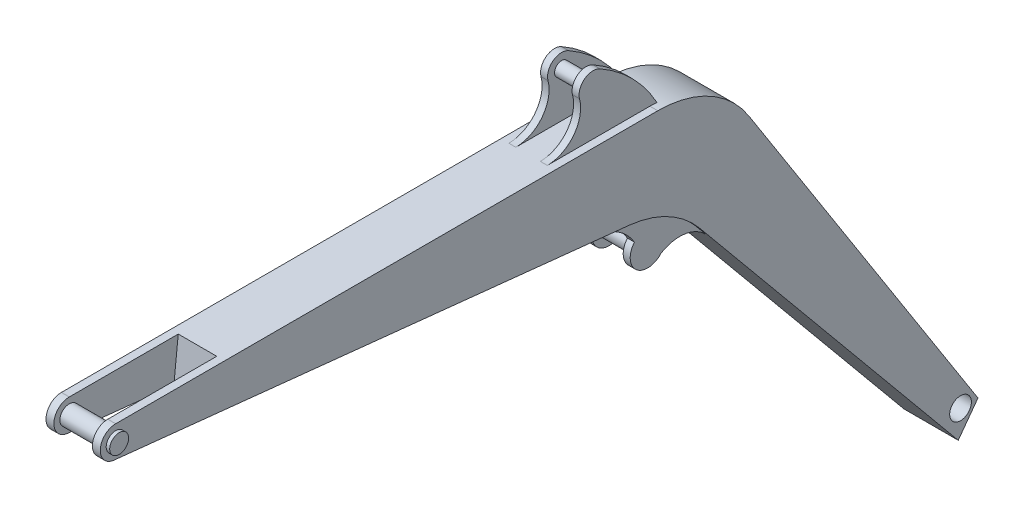
SolidWorks part; units mm, degrees
material "Chrome Stainless Steel"
ref_plane "Plano frontal" through (0, 0, 0) normal (0, 0, 1) x (1, 0, 0)
ref_plane "Plano superior" through (0, 0, 0) normal (0, 1, 0) x (1, 0, 0)
ref_plane "Plano direito" through (0, 0, 0) normal (1, 0, 0) x (0, 0, -1)
sketch "Sketch1" plane through (0, 0, 0) normal (1, 0, 0) x (0, 0, -1)
  line L0 (-1649, 84.5752) -> (0, 0) construction
  line L1 (0, 0) -> (784.5035, -1077.2462) construction
  line L2 (-1649, 128.5752) -> (-100.623, 128.5752)
  line L3 (-1653.5993, 40.8162) -> (-181.4137, -113.9167)
  line L4 (18.502, -221.1916) -> (757.4789, -1115.6067)
  line L5 (158.9567, -13.6468) -> (813.9018, -1039.1773)
  line L6 (813.9018, -1039.1773) -> (757.4789, -1115.6067)
  arc A0 (-1649, 128.5752) -> (-1653.5993, 40.8162) centre (-1649, 84.5752) ccw
  circle A1 centre (764, -1039.4248) radius 31
  arc A2 (-181.4137, -113.9167) -> (18.502, -221.1916) centre (-212.7722, -412.2733) cw
  arc A3 (158.9567, -13.6468) -> (-100.623, 128.5752) centre (-100.623, -179.4248) ccw
  dimension "D1" = 129
  dimension "D3" = 1290
  dimension "D4" = 62
  dimension "D8" = 7
  dimension "D2" = 88
  dimension "D9" = 300
  dimension "D14" = 308
  dimension "D5" = 1124
  dimension "D6" = 2413
  dimension "D7" = 6
  dimension "D10" = 76
  dimension "D11" = 95
  dimension "D12" = 40
  dimension "D13" = 1649
extrude "Boss-Extrude1" add sketch "Sketch1" along normal mid plane 155
sketch "Sketch2" plane through (0, 0, 0) normal (1, 0, 0) x (0, 0, -1)
  line L0 (-1337.7808, 128.5752) -> (-1350.221, 8.9299)
  line L1 (-100.623, 128.5752) -> (-1649, 128.5752) construction
  line L2 (-1653.5993, 40.8162) -> (-181.4137, -113.9167) construction
  line L3 (-1649, 84.5752) -> (0, 0) construction
  line L4 (-1653.5993, 40.8162) -> (-1350.221, 8.9299)
  line L5 (-1337.7808, 128.5752) -> (-1649, 128.5752)
  arc A0 (-1649, 128.5752) -> (-1653.5993, 40.8162) centre (-1649, 84.5752) ccw construction
  arc A1 (-1649, 128.5752) -> (-1653.5993, 40.8162) centre (-1649, 84.5752) ccw
  dimension "D1" = 87
  dimension "D2" = 305
extrude "Cut-Extrude1" cut sketch "Sketch2" against normal mid plane 110 contours L4 L0 L5 A1
sketch "Sketch3" plane through (0, 0, 0) normal (1, 0, 0) x (0, 0, -1)
  circle A0 centre (-1649, 84.5752) radius 27
  dimension "D1" = 54
extrude "Boss-Extrude2" add sketch "Sketch3" along normal mid plane 175
sketch "Sketch4" plane through (0, 0, 0) normal (1, 0, 0) x (0, 0, -1)
  line L0 (-100.623, 128.5752) -> (-1649, 128.5752) construction
  line L1 (-100.623, 128.5752) -> (-393.6484, 128.5752)
  circle A0 centre (-263, 257.5752) radius 20
  circle A1 centre (-1649, 84.5752) radius 27 construction
  arc A2 (-243.3632, 292.4234) -> (-301.7106, 247.5011) centre (-263, 257.5752) ccw
  arc A3 (-301.7106, 247.5011) -> (-393.6484, 128.5752) centre (-393.6484, 223.5752) cw
  arc A4 (-243.3632, 292.4234) -> (-80.6484, 127.9268) centre (-450.5312, -75.2252) cw
  arc A5 (158.9567, -13.6468) -> (-100.623, 128.5752) centre (-100.623, -179.4248) ccw construction
  arc A6 (-80.6484, 127.9268) -> (-100.623, 128.5752) centre (-100.623, -179.4248) ccw
  dimension "D3" = 40
  dimension "D4" = 80
  dimension "D6" = 422
  dimension "D7" = 95
  dimension "D1" = 1386
  dimension "D2" = 129
  dimension "D5" = 313
extrude "Boss-Extrude3" add sketch "Sketch4" along normal blind 20 from offset 35
mirror "Mirror1" about plane through (0, 0, 0) normal (1, 0, 0) of bodies 104
sketch "Sketch5" plane through (0, 0, 0) normal (1, 0, 0) x (0, 0, -1)
  line L0 (-1653.5993, 40.8162) -> (-181.4137, -113.9167) construction
  line L1 (18.502, -221.1916) -> (757.4789, -1115.6067) construction
  line L2 (18.502, -221.1916) -> (49.2646, -258.4248)
  line L3 (-248.3291, -106.8836) -> (-181.4137, -113.9167)
  circle A0 centre (-117, -208.4248) radius 28
  circle A1 centre (-263, 257.5752) radius 20 construction
  circle A2 centre (-1649, 84.5752) radius 27 construction
  arc A3 (-154.7441, -175.6318) -> (-79.2559, -241.2179) centre (-117, -208.4248) ccw
  arc A4 (-248.3291, -106.8836) -> (-154.7441, -175.6318) centre (-283.4187, -252.7217) cw
  arc A5 (-79.2559, -241.2179) -> (49.2646, -258.4248) centre (-25.6164, -329.1485) cw
  arc A6 (18.502, -221.1916) -> (-181.4137, -113.9167) centre (-212.7722, -412.2733) ccw construction
  arc A7 (18.502, -221.1916) -> (-181.4137, -113.9167) centre (-212.7722, -412.2733) ccw
  dimension "D1" = 466
  dimension "D3" = 56
  dimension "D4" = 100
  dimension "D5" = 150
  dimension "D6" = 103
  dimension "D2" = 1532
  dimension "D7" = 100
extrude "Boss-Extrude4" add sketch "Sketch5" along normal blind 20 from offset 45
mirror "Mirror2" about plane through (0, 0, 0) normal (1, 0, 0) of bodies 106
sketch "Sketch6" plane through (0, 0, 0) normal (1, 0, 0) x (0, 0, -1)
  circle A0 centre (-263, 257.5752) radius 20
  dimension "D1" = 40
extrude "Boss-Extrude5" add sketch "Sketch6" along normal mid plane 110
sketch "Sketch7" plane through (0, 0, 0) normal (1, 0, 0) x (0, 0, -1)
  circle A0 centre (-117, -208.4248) radius 28
  dimension "D1" = 56
extrude "Boss-Extrude6" add sketch "Sketch7" along normal mid plane 130
